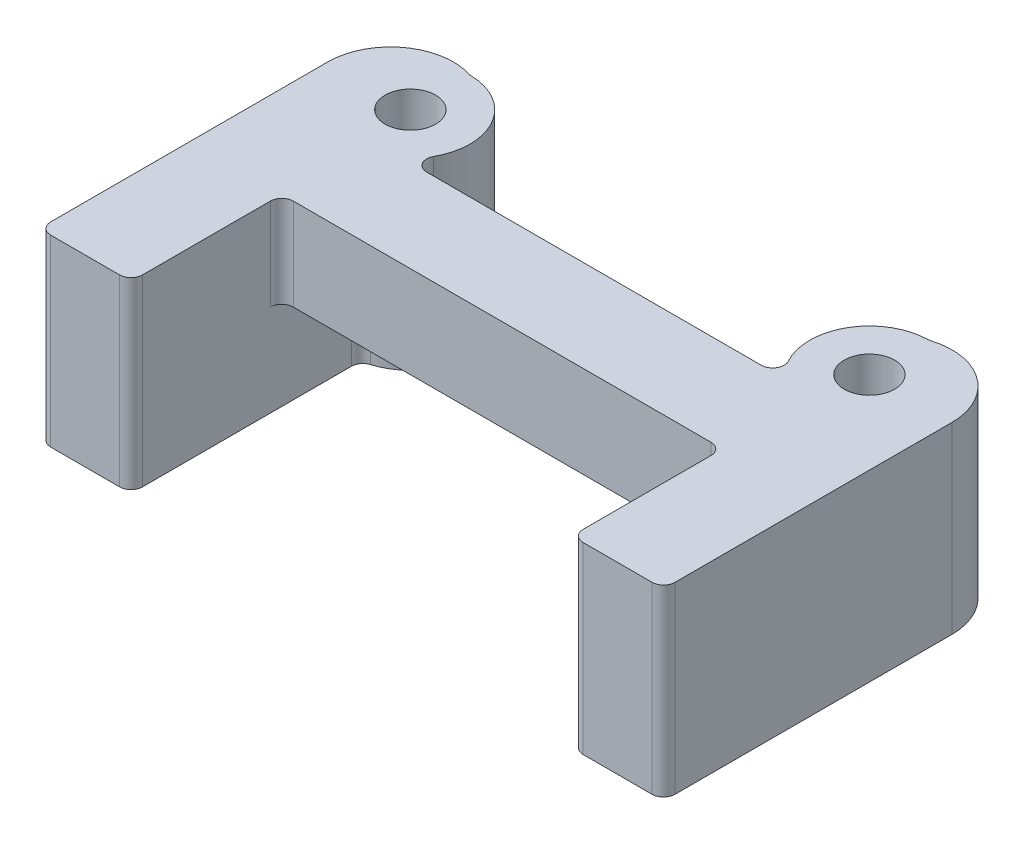
SolidWorks part; units mm, degrees
ref_plane "Front Plane" through (0, 0, 0) normal (0, 0, 1) x (1, 0, 0)
ref_plane "Top Plane" through (0, 0, 0) normal (0, 1, 0) x (1, 0, 0)
ref_plane "Right Plane" through (0, 0, 0) normal (1, 0, 0) x (0, 0, -1)
sketch "Sketch1" plane through (0, 0, 0) normal (0, 1, 0) x (1, 0, 0)
  line L0 (2.6, 0) -> (3.6, 0) construction
  line L1 (3.6, 0) -> (3.6, -12.569)
  line L2 (3.6, -12.569) -> (-0.4, -12.569)
  line L3 (-0.4, -12.569) -> (-0.4, -2.569)
  arc A0 (0, 2.6) -> (-0.4, -2.569) centre (0, 0) ccw
  circle A1 centre (0, 0) radius 1.1
  arc A2 (0, 2.6) -> (3.6, 0) centre (0.8611, 0) cw
  arc A3 (-0.4, -2.569) -> (2.6, 0) centre (0, 0) ccw construction
  arc A4 (2.6, 0) -> (0, 2.6) centre (0, 0) ccw construction
  dimension "D1" = 5.2
  dimension "D2" = 2.2
  dimension "D3" = 1
  dimension "D4" = 4
  dimension "D5" = 10
extrude "Base" add sketch "Sketch1" along normal blind 8
sketch "Sketch2" plane through (0, 8, 0) normal (0, 1, 0) x (1, 0, 0)
  line L0 (0, 0) -> (0, -2) construction
  line L1 (0, -2) -> (-10, -2)
  line L2 (-10, -2) -> (-10, -6)
  line L3 (-10, -6) -> (0, -6)
  line L4 (0, -6) -> (0, -2)
  point P5 (0, 0)
  arc M5 (0, 2.6) -> (-0.4, -2.569) centre (0, 0) ccw
  line M6 (-0.4, -2.569) -> (-0.4, -12.569)
  dimension "D1" = 2
  dimension "D2" = 4
  dimension "D3" = 10
extrude "Boss-Extrude2" add sketch "Sketch2" against normal blind 4 contours L2 L3 L1 M6 M5
ref_plane "Plane1" through (-10, 0, 0) normal (-1, 0, 0) x (0, 0, 1)
mirror "Mirror2" about plane through (-10, 0, 0) normal (-1, 0, 0) of bodies 102
fillet "Fillet1" radius 0.5 12 edges at (-20, 4, -2.6) (0, 4, -2.6) (-0.4, 2, 2.569) (-19.6, 2, 2.569) (-18.3387, 6, 2) (-1.6613, 6, 2) (3.6, 4, 12.569) (-0.4, 4, 12.569) (-0.4, 6, 6) (-19.6, 6, 6) (-23.6, 4, 12.569) (-19.6, 4, 12.569)
